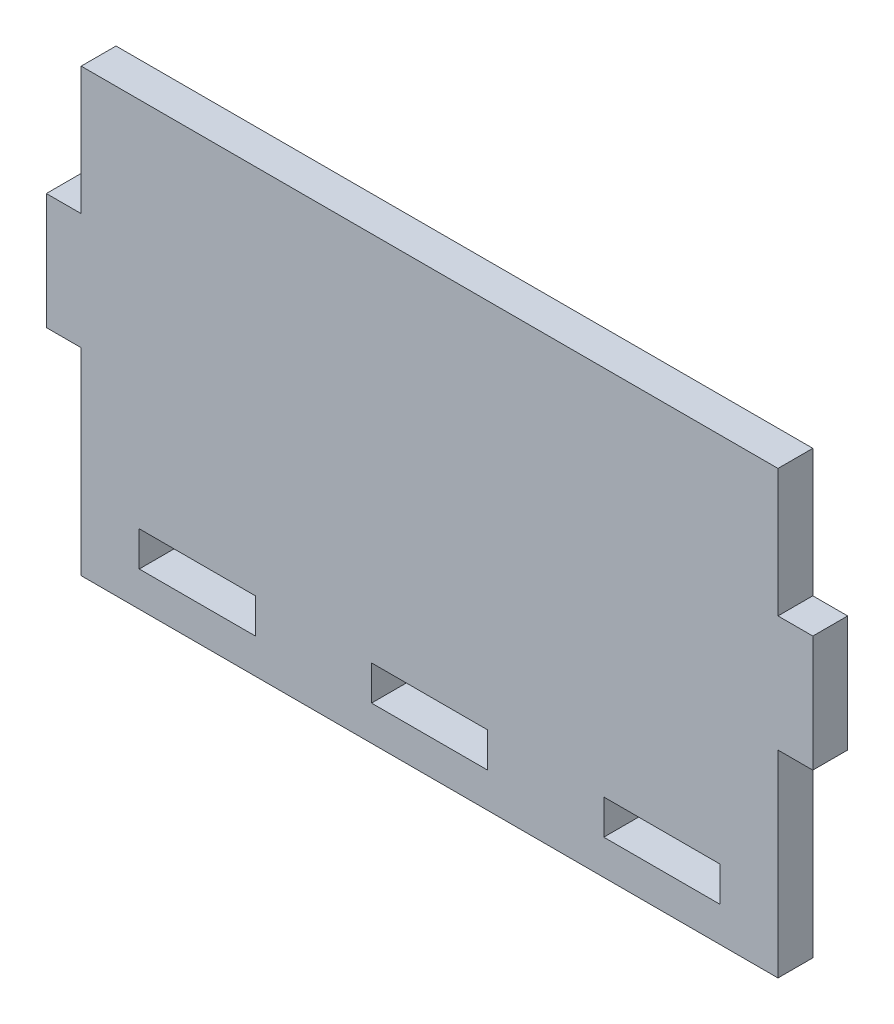
SolidWorks part; units mm, degrees
ref_plane "Front Plane" through (0, 0, 0) normal (0, 0, 1) x (1, 0, 0)
ref_plane "Top Plane" through (0, 0, 0) normal (0, 1, 0) x (1, 0, 0)
ref_plane "Right Plane" through (0, 0, 0) normal (1, 0, 0) x (0, 0, -1)
sketch "Sketch1" plane through (0, 0, 0) normal (0, 0, 1) x (1, 0, 0)
  line L0 (-2.8507, 15.0679) -> (-2.8507, -39.6784) construction
  line L1 (-32.8507, 15.0679) -> (27.1493, 15.0679)
  line L2 (-32.8507, 15.0679) -> (-32.8507, -22.9321)
  line L3 (-32.8507, -22.9321) -> (27.1493, -22.9321)
  line L4 (27.1493, 15.0679) -> (27.1493, -22.9321)
  line L5 (27.1493, 4.0679) -> (30.1493, 4.0679)
  line L6 (30.1493, 4.0679) -> (30.1493, -5.9321)
  line L7 (30.1493, -5.9321) -> (27.1493, -5.9321)
  line L8 (-7.8507, -16.9321) -> (2.1493, -16.9321)
  line L9 (22.1493, -16.9321) -> (12.1493, -16.9321)
  line L10 (22.1493, -16.9321) -> (22.1493, -19.9321)
  line L11 (22.1493, -19.9321) -> (12.1493, -19.9321)
  line L12 (12.1493, -16.9321) -> (12.1493, -19.9321)
  line L13 (2.1493, -16.9321) -> (2.1493, -19.9321)
  line L14 (2.1493, -19.9321) -> (-7.8507, -19.9321)
  line L15 (-35.8507, -5.9321) -> (-32.8507, -5.9321)
  line L16 (-35.8507, 4.0679) -> (-35.8507, -5.9321)
  line L17 (-32.8507, 4.0679) -> (-35.8507, 4.0679)
  line L18 (-7.8507, -16.9321) -> (-7.8507, -19.9321)
  line L19 (-17.8507, -16.9321) -> (-17.8507, -19.9321)
  line L20 (-27.8507, -19.9321) -> (-17.8507, -19.9321)
  line L21 (-27.8507, -16.9321) -> (-27.8507, -19.9321)
  line L22 (-27.8507, -16.9321) -> (-17.8507, -16.9321)
  point P23 (-2.8507, -19.9321)
  point P28 (-2.8507, -16.9321)
  dimension "D1" = 60
  dimension "D2" = 38
  dimension "D3" = 11
  dimension "D4" = 3
  dimension "D5" = 10
  dimension "D6" = 17
  dimension "D7" = 10
  dimension "D8" = 3
  dimension "D9" = 3
  dimension "D10" = 5
  dimension "D11" = 10
  dimension "D12" = 3
  dimension "D13" = 3
  dimension "D14" = 5
extrude "Boss-Extrude1" add sketch "Sketch1" along normal blind 3 contours L0 L1 L2 L3 L14 L18 L8 L21 L22 L19 L20 | L1 L0 L8 L13 L14 L3 L4 L12 L9 L10 L11 | L2 L17 L16 L15 | L7 L6 L5 L4
